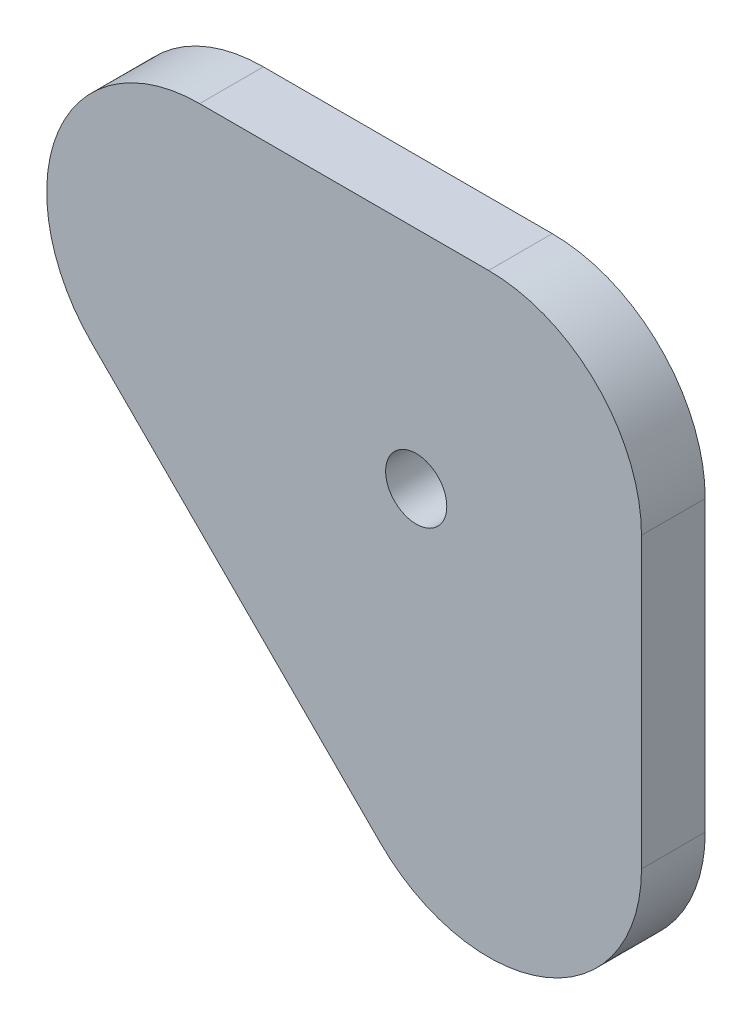
SolidWorks part; units mm, degrees
ref_plane "Front Plane" through (0, 0, 0) normal (0, 0, 1) x (1, 0, 0)
ref_plane "Top Plane" through (0, 0, 0) normal (0, 1, 0) x (1, 0, 0)
ref_plane "Right Plane" through (0, 0, 0) normal (1, 0, 0) x (0, 0, -1)
sketch "Sketch1" plane through (0, 0, 0) normal (0, 0, 1) x (1, 0, 0)
  line B0 (-69.4771, -61.1582) -> (-92.1461, -61.1582)
  arc B1 (-57.4771, -73.1582) -> (-69.4771, -61.1582) centre (-69.4771, -73.1582) ccw
  line B2 (-57.4771, -95.8273) -> (-57.4771, -73.1582)
  arc B3 (-77.9623, -104.3126) -> (-57.4771, -95.8273) centre (-69.4771, -95.8273) ccw
  line B4 (-100.6314, -81.6435) -> (-77.9623, -104.3126)
  arc B5 (-92.1461, -61.1582) -> (-100.6314, -81.6435) centre (-92.1461, -73.1582) ccw
  circle B6 centre (-75.1547, -78.8359) radius 2.4
sketch_block_instance "903_Triangle_x12_6mm_Ferro-1"
sketch_block "903_Triangle_x12_6mm_Ferro"
extrude "Boss-Extrude1" add sketch "Sketch1" along normal blind 5
sketch "Sketch2" plane through (0, 0, 0) normal (0, 0, -1) x (-1, 0, 0)
  line L0 (92.1461, -66.1582) -> (69.4771, -66.1582)
  line L2 (74.4268, -100.777) -> (97.0959, -78.108)
  line L3 (92.1461, -61.1582) -> (69.4771, -61.1582)
  line L4 (57.4771, -73.1582) -> (57.4771, -95.8273)
  line L5 (77.9623, -104.3126) -> (100.6314, -81.6435)
  line L6 (92.1461, -61.1582) -> (69.4771, -61.1582)
  line L7 (57.4771, -73.1582) -> (57.4771, -95.8273)
  line L8 (77.9623, -104.3126) -> (100.6314, -81.6435)
  line L9 (62.4818, -100.7013) -> (97.0248, -66.1582)
  line L10 (62.4771, -95.8273) -> (62.4818, -100.7013)
  line L11 (92.1461, -66.1582) -> (97.0248, -66.1582)
  line L12 (62.4771, -95.8273) -> (62.4771, -73.1582)
  line L13 (62.4771, -73.1582) -> (62.4771, -95.8273) construction
  arc A0 (69.4771, -66.1582) -> (62.4771, -73.1582) centre (69.4771, -73.1582) ccw
  arc A3 (100.6314, -81.6435) -> (92.1461, -61.1582) centre (92.1461, -73.1582) ccw
  arc A4 (69.4771, -61.1582) -> (57.4771, -73.1582) centre (69.4771, -73.1582) ccw
  arc A5 (57.4771, -95.8273) -> (77.9623, -104.3126) centre (69.4771, -95.8273) ccw
  arc A6 (100.6314, -81.6435) -> (92.1461, -61.1582) centre (92.1461, -73.1582) ccw
  arc A7 (69.4771, -61.1582) -> (57.4771, -73.1582) centre (69.4771, -73.1582) ccw
  arc A8 (57.4771, -95.8273) -> (77.9623, -104.3126) centre (69.4771, -95.8273) ccw
  arc A9 (97.0959, -78.108) -> (92.1461, -66.1582) centre (92.1461, -73.1582) ccw construction
  arc A12 (62.4771, -95.8273) -> (74.4268, -100.777) centre (69.4771, -95.8273) ccw construction
  dimension "D3" = 8.5
  dimension "D1" = 0
  dimension "D2" = 5
